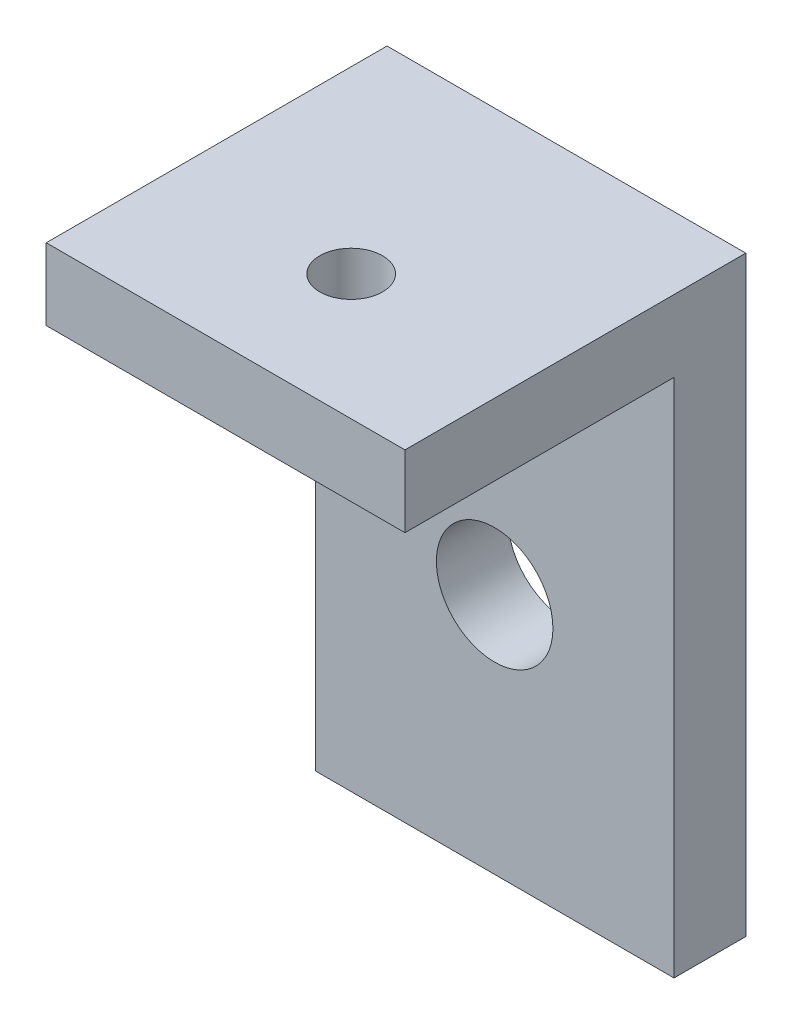
SolidWorks part; units mm, degrees
ref_plane "Ön Düzlem" through (0, 0, 0) normal (0, 0, 1) x (1, 0, 0)
ref_plane "Üst Düzlem" through (0, 0, 0) normal (0, 1, 0) x (1, 0, 0)
ref_plane "Sağ Düzlem" through (0, 0, 0) normal (1, 0, 0) x (0, 0, -1)
sketch "Çizim1" plane through (0, 0, 0) normal (0, 0, 1) x (1, 0, 0)
  line L0 (0, 0) -> (0, 33)
  line L1 (0, 33) -> (20, 33)
  line L2 (20, 33) -> (20, 0)
  line L3 (20, 0) -> (0, 0)
  circle A0 centre (10, 13.5) radius 3.25
  dimension "D3" = 19.5
  dimension "D1" = 20
  dimension "D2" = 33
extrude "Yükseklik-Ekstrüzyon1" add sketch "Çizim1" along normal blind 4
sketch "Çizim2" plane through (0, 0, 4) normal (0, 0, 1) x (1, 0, 0)
  line L0 (20, 0) -> (20, 33) construction
  line L1 (0, 33) -> (20, 33)
  line L2 (0, 33) -> (0, 29)
  line L3 (0, 29) -> (20, 29)
  line L4 (20, 33) -> (20, 29)
  dimension "D1" = 4
extrude "Yükseklik-Ekstrüzyon2" add sketch "Çizim2" along normal blind 15
sketch "Çizim3" plane through (0, 33, 0) normal (0, 1, 0) x (1, 0, 0)
  line L0 (20, -19) -> (0, -19) construction
  circle A0 centre (10, -12) radius 1.75
  dimension "D1" = 3.5
  dimension "D2" = 7
extrude "Kes-Ekstrüzyon1" cut sketch "Çizim3" against normal blind 15
